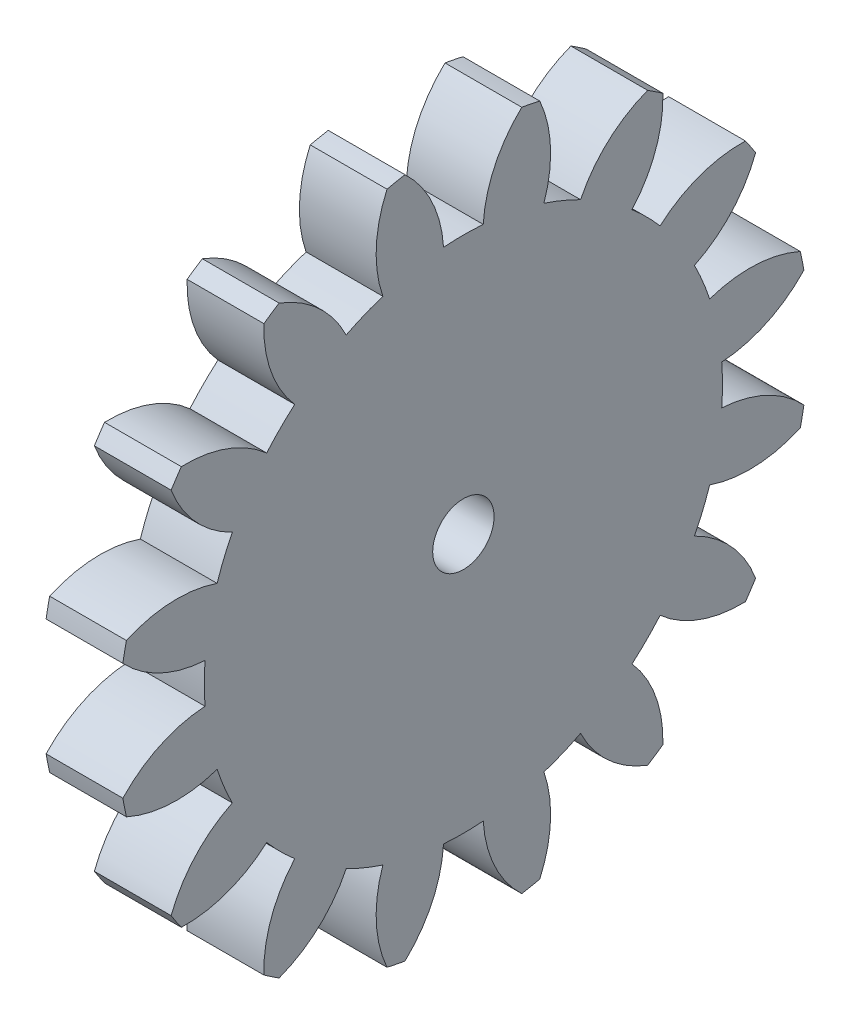
SolidWorks part; units mm, degrees
ref_plane "Plane1" through (0, 0, 0) normal (0, 0, 1) x (1, 0, 0)
ref_plane "Plane2" through (0, 0, 0) normal (0, 1, 0) x (1, 0, 0)
ref_plane "Plane3" through (0, 0, 0) normal (1, 0, 0) x (0, 0, -1)
sketch "HoldingSke" plane through (0, 0, 0) normal (0, 1, 0) x (1, 0, 0)
  line L0 (0, 0) -> (0.1923, -0.0551)
  line L1 (-15, 0) -> (100, 0) construction
  line L2 (0, 0) -> (-2.1039, 2.3779)
  line L3 (0, 0) -> (-11.863, 4.5341)
  line L4 (0, 0) -> (8.3015, 2.3804)
  line L5 (0, 0) -> (-18.7391, -6.9891)
  line L6 (0, 0) -> (-8.2896, -5.593)
  line L7 (-2.1039, 2.3779) -> (2.2011, 21.9091)
  line L8 (-76.2, 54.61) -> (-74.8, 54.61)
  line L9 (-71.009, 38.7566) -> (-53.1078, 45.2721)
  line L10 (-76.2, 71.12) -> (104.1128, 71.12)
  line L11 (0, 0) -> (-10, 0)
  line L12 (-76.2, 101.6) -> (-76.033, 101.6)
  line L13 (24.9733, 27.94) -> (52.9518, 28.4284)
  line L14 (24.9733, 27.94) -> (24.9743, 27.94)
  line L15 (24.9733, 27.94) -> (100.4006, 29.5858)
  line L16 (-63.627, -5) -> (-12.827, -5)
  circle A0 centre (0, 0) radius 4
  circle A1 centre (0, 0) radius 10
  circle A2 centre (0, 0) radius 10
  circle A3 centre (0, 0) radius 4
  dimension "MHD" = 20
  dimension "Hub_dia" = 20
  dimension "Bore" = 8
  dimension "MBD" = 8
  dimension "Num_teeth" = 16
  dimension "Pitch" = 0.2
  dimension "Overall_len" = 20
  dimension "Show_teeth" = 16
  dimension "Thickness" = 10
  dimension "OAL" = 20.0001
  dimension "T_dim" = 1.4
  dimension "Ap" = 20
  dimension "H" = 19.05
  dimension "Pitch_radius" = 180.3128
  dimension "Width" = 10
  dimension "Backlash" = 0.167
  dimension "Addendum_fac" = 1
  dimension "Dedendum_fac" = 1.25
  dimension "Clearance_fac" = 0.25
  dimension "Dedendum_add" = 0.001
  dimension "Module" = 5
sketch "BasProSke" plane through (0, 0, 0) normal (0, 1, 0) x (1, 0, 0)
  line L0 (-10, 0) -> (60, 0) construction
  line L1 (0, 0) -> (0, 45)
  line L2 (0, 0) -> (10, 0)
  line L3 (10, 0) -> (10, 45)
  line L4 (10, 45) -> (0, 45)
  dimension "Thickness" = 10
  dimension "Diameter" = 90
revolve "Base-Revolve" add sketch "BasProSke" angle 360 about L0
sketch "TooCutSke" plane through (0, 0, 0) normal (1, 0, 0) x (0, 0, -1)
  line L1 (0, 0) -> (0, 107) construction
  line L2 (0, 0) -> (-4.2127, 39.7775) construction
  line L3 (0, 0) -> (-15.5429, 78.1393) construction
  line L4 (-4.2127, 39.7775) -> (-7.7714, 39.0697) construction
  arc A0 (2.5852, 33.6498) -> (-2.5852, 33.6498) centre (0, 0) ccw
  arc A1 (7.6282, 44.3745) -> (-7.6282, 44.3745) centre (0, 0) ccw
  circle A2 centre (0, 0) radius 40 construction
  circle A3 centre (0, 0) radius 37.5877 construction
  arc A4 (-2.5852, 33.6498) -> (-7.6282, 44.3745) centre (-18.5563, 32.6879) ccw
  arc A5 (7.6282, 44.3745) -> (2.5852, 33.6498) centre (18.5563, 32.6879) ccw
  dimension "Root_dia" = 67.498
  dimension "Overcut_dia" = 90.0508
  dimension "Pitch_dia" = 80
  dimension "Base_dia" = 75.1754
  dimension "Flank_rad" = 16
  dimension "Half_ang" = 11.25
  dimension "Half_CT" = 3.6284
extrude "ToothCut" cut sketch "TooCutSke" along normal through all
fillet "Breaks" [suppressed] radius 0.1
fillet "RootFillets" [suppressed] radius 1.251
pattern_circular "TeethCuts" count 16 every 22.5 about axis through (-10, 0, 0) along (1, 0, 0) of "ToothCut", "RootFillets", "Breaks"
sketch "HubNeaOneSke" plane through (0, 0, 0) normal (-1, 0, 0) x (0, 0, 1)
  circle A0 centre (0, 0) radius 10
  dimension "Diameter" = 20
extrude "HubNearOne" add sketch "HubNeaOneSke" along normal blind 10.0001
sketch "HubNeaBotSke" plane through (0, 0, 0) normal (-1, 0, 0) x (0, 0, 1)
  circle A0 centre (0, 0) radius 10
  dimension "Diameter" = 20
extrude "HubNearBoth" [suppressed] add sketch "HubNeaBotSke" along normal blind 5
ref_plane "FarPln" through (10, 0, 0) normal (1, 0, 0) x (0, 0, -1)
sketch "HubFarSke" plane through (10, 0, 0) normal (1, 0, 0) x (0, 0, -1)
  circle A0 centre (0, 0) radius 10
  dimension "Diameter" = 20
extrude "HubFar" [suppressed] add sketch "HubFarSke" along normal blind 5
sketch "BorSke" plane through (0, 0, 0) normal (1, 0, 0) x (0, 0, -1)
  circle A0 centre (0, 0) radius 4
  dimension "Diameter" = 8
extrude "Bore" cut sketch "BorSke" along normal mid plane 40.0001
sketch "KeySke" plane through (0, 0, 0) normal (1, 0, 0) x (0, 0, -1)
  line L0 (-1.5, 0) -> (-1.5, 5.4)
  line L1 (-1.5, 5.4) -> (1.5, 5.4)
  line L2 (1.5, 5.4) -> (1.5, 0)
  line L3 (0, 0) -> (0, 34) construction
  line L4 (-1.5, 0) -> (1.5, 0)
  dimension "Offset" = 5.4
  dimension "Width" = 3
extrude "Keyway" [suppressed] cut sketch "KeySke" along normal mid plane 40.0001
pattern_circular "Keyway2" [suppressed] count 2 every 90 about axis through (-10, 0, 0) along (1, 0, 0)
equation "' \"Module@HoldingSke\" = 6.35"
equation "' \"Num_teeth@HoldingSke\" = 12"
equation "' \"Ap@HoldingSke\" =  20"
equation "' \"Ap@HoldingSke\" = 20"
equation "' \"Width@HoldingSke\" = 0.5 * 25.4"
equation "' \"Hub_dia@HoldingSke\"= 1 * 25.4"
equation "' \"Hub_dia@HoldingSke\" = 1 * 25.4"
equation "' \"Overall_len@HoldingSke\" = 1.0 * 25.4"
equation "' \"Bore@HoldingSke\" = 0.75 * 25.4"
equation "' \"T_dim@HoldingSke\" = 0.1 * 25.4"
equation "' \"Width@KeySke\" = 0.25 * 25.4"
equation "' \"Show_teeth@HoldingSke\" = 13"
equation "' \"Backlash@HoldingSke\" = 0.009 * 25.4"
equation "' \"Addendum_fac@HoldingSke\" = 1.0"
equation "' \"Dedendum_fac@HoldingSke\" = 1.25"
equation "' \"Dedendum_add@HoldingSke\" = 0.00005 * 25.4"
equation "' \"Clearance_fac@HoldingSke\" = 0.25"
equation "\"Pitch@HoldingSke\" = 1 / \"Module@HoldingSke\""
equation "\"Overcut_dia@TooCutSke\" = (\"Num_teeth@HoldingSke\" + 2 * \"Addendum_fac@HoldingSke\") / \"Pitch@HoldingSke\" + 0.002 * 25.4"
equation "\"Pitch_dia@TooCutSke\" = \"Num_teeth@HoldingSke\" / \"Pitch@HoldingSke\""
equation "\"Base_dia@TooCutSke\" = \"Num_teeth@HoldingSke\" / \"Pitch@HoldingSke\" * cos((\"Ap@HoldingSke\"  * 3.14159265 / 180))"
equation "\"Root_dia@TooCutSke\" = (\"Num_teeth@HoldingSke\" + 2) / \"Pitch@HoldingSke\" - 2 * (\"Addendum_fac@HoldingSke\" + \"Dedendum_fac@HoldingSke\") / \"Pitch@HoldingSke\" - \"Dedendum_add@HoldingSke\" * 2"
equation "\"Half_ang@TooCutSke\" = 180 / \"Num_teeth@HoldingSke\""
equation "\"Half_CT@TooCutSke\" = \"Num_teeth@HoldingSke\" / \"Pitch@HoldingSke\" * sin((3.14159265 / 2 / \"Num_teeth@HoldingSke\")) / 2 - 7 * \"Backlash@HoldingSke\" / 4"
equation "\"Flank_rad@TooCutSke\" = \"Num_teeth@HoldingSke\" / \"Pitch@HoldingSke\" / 5"
equation "\"Radius@RootFillets\" = \"Clearance_fac@HoldingSke\" / \"Pitch@HoldingSke\" + \"Dedendum_add@HoldingSke\""
equation "\"Break_rad@Breaks\" = 0.02 / \"Pitch@HoldingSke\""
equation "\"Thickness@HoldingSke\" = \"Width@HoldingSke\""
equation "\"OAL@HoldingSke\" = \"Thickness@HoldingSke\""
equation "\"MHD@HoldingSke\" = (\"Num_teeth@HoldingSke\" + 2) / \"Pitch@HoldingSke\" - 2 * (\"Addendum_fac@HoldingSke\" + \"Dedendum_fac@HoldingSke\")  / \"Pitch@HoldingSke\" - \"Dedendum_add@HoldingSke\" * 2"
equation "\"MBD@HoldingSke\" = (\"Num_teeth@HoldingSke\" + 2) / \"Pitch@HoldingSke\" - 2 * (\"Addendum_fac@HoldingSke\" + \"Dedendum_fac@HoldingSke\")  / \"Pitch@HoldingSke\" - \"Dedendum_add@HoldingSke\" * 2 - 0.002 * 25.4"
equation "\"MHD@HoldingSke\" = ((sgn( \"MHD@HoldingSke\" - \"Hub_dia@HoldingSke\" )-1)*( \"MHD@HoldingSke\" - \"Hub_dia@HoldingSke\" ))/-2+ \"Hub_dia@HoldingSke\""
equation "\"MBD@HoldingSke\" = ((sgn( \"MBD@HoldingSke\" - \"Bore@HoldingSke\" )-1)*( \"MBD@HoldingSke\" - \"Bore@HoldingSke\" ))/-2+ \"Bore@HoldingSke\""
equation "\"OAL@HoldingSke\" = ((sgn( \"OAL@HoldingSke\" - \"Overall_len@HoldingSke\" )+1)*( \"OAL@HoldingSke\" - \"Overall_len@HoldingSke\" ))/2 + \"Overall_len@HoldingSke\" + 0.000002 * 25.4"
equation "\"Num_teeth@TeethCuts\" = int( \"Show_teeth@HoldingSke\" ) + 1"
equation "\"Num_teeth@TeethCuts\" = ((sgn( \"Num_teeth@TeethCuts\" - \"Num_teeth@HoldingSke\" )-1)*( \"Num_teeth@TeethCuts\" - \"Num_teeth@HoldingSke\" ))/-2+ \"Num_teeth@HoldingSke\""
equation "\"Num_teeth@TeethCuts\" = ((sgn( \"Num_teeth@TeethCuts\" - 2.0)+1)*( \"Num_teeth@TeethCuts\" - 2.0))/2 +2.0"
equation "\"Angle@TeethCuts\" = 360.0 / \"Num_teeth@HoldingSke\""
equation "\"Diameter@BasProSke\" = (\"Num_teeth@HoldingSke\" + 2 * \"Addendum_fac@HoldingSke\") / \"Pitch@HoldingSke\""
equation "\"Thickness@BasProSke\"  = \"Thickness@HoldingSke\""
equation "' \"Fillet_rad@BasProSke\" =  \"Thickness@HoldingSke\" * 0.05"
equation "' \"Fillet_rad@BasProSke\" = \"Thickness@HoldingSke\" * 0.05"
equation "\"MHD@HoldingSke\" = ((sgn( \"MHD@HoldingSke\" - \"Root_dia@TooCutSke\" )-1)*( \"MHD@HoldingSke\" - \"Root_dia@TooCutSke\" ))/-2+ \"Root_dia@TooCutSke\""
equation "\"Diameter@HubNeaOneSke\" = \"MHD@HoldingSke\""
equation "\"Length@HubNearOne\" = \"OAL@HoldingSke\" - \"Thickness@BasProSke\""
equation "\"Diameter@HubNeaBotSke\" = \"MHD@HoldingSke\""
equation "\"Length@HubNearBoth\" = ( \"OAL@HoldingSke\" - \"Thickness@BasProSke\" ) / 2.0"
equation "\"Thickness@FarPln\" = \"Thickness@BasProSke\""
equation "\"Diameter@HubFarSke\" = \"MHD@HoldingSke\""
equation "\"Length@HubFar\" = ( \"OAL@HoldingSke\" - \"Thickness@BasProSke\" ) / 2.0"
equation "\"Diameter@BorSke\" = \"MBD@HoldingSke\""
equation "\"D1@Bore\" = \"OAL@HoldingSke\" * 2.0"
equation "\"D1@Keyway\" = \"OAL@HoldingSke\" * 2.0"
equation "\"Offset@KeySke\" = \"T_dim@HoldingSke\" + \"MBD@HoldingSke\" / 2.0"
